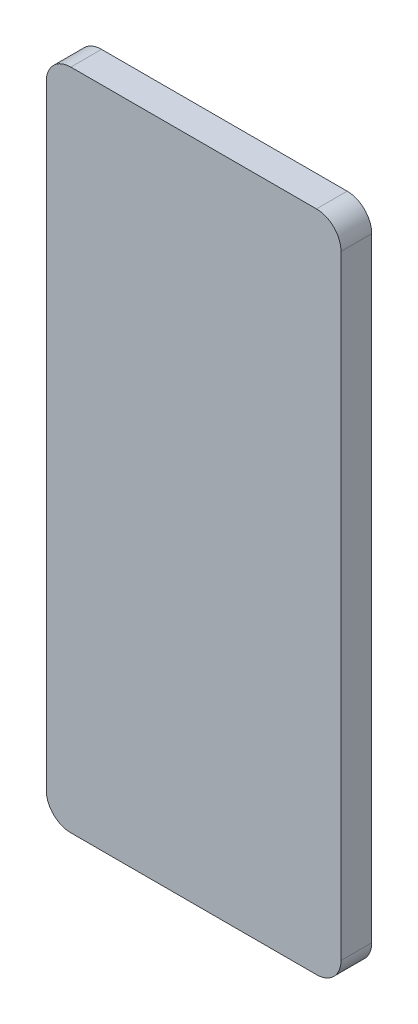
SolidWorks part; units mm, degrees
material "1.0553 (S355J0)"
ref_plane "Front Plane" through (0, 0, 0) normal (0, 0, 1) x (1, 0, 0)
ref_plane "Top Plane" through (0, 0, 0) normal (0, 1, 0) x (1, 0, 0)
ref_plane "Right Plane" through (0, 0, 0) normal (1, 0, 0) x (0, 0, -1)
sketch "Sketch1" plane through (0, 0, 0) normal (0, 0, 1) x (1, 0, 0)
  line L1 (-20, -54) -> (20, -54)
  line L2 (-24, -50) -> (-24, 50)
  line L3 (-20, 54) -> (20, 54)
  line L4 (24, -50) -> (24, 50)
  line L5 (-24, -54) -> (24, 54) construction
  line L6 (-24, 54) -> (24, -54) construction
  arc A0 (-20, -54) -> (-24, -50) centre (-20, -50) cw
  arc A1 (20, -54) -> (24, -50) centre (20, -50) ccw
  arc A2 (20, 54) -> (24, 50) centre (20, 50) cw
  arc A3 (-24, 50) -> (-20, 54) centre (-20, 50) cw
  point P0 (0, 0)
  dimension "D3" = 4
  dimension "D1" = 108
  dimension "D2" = 48
extrude "Boss-Extrude1" add sketch "Sketch1" against normal blind 5
